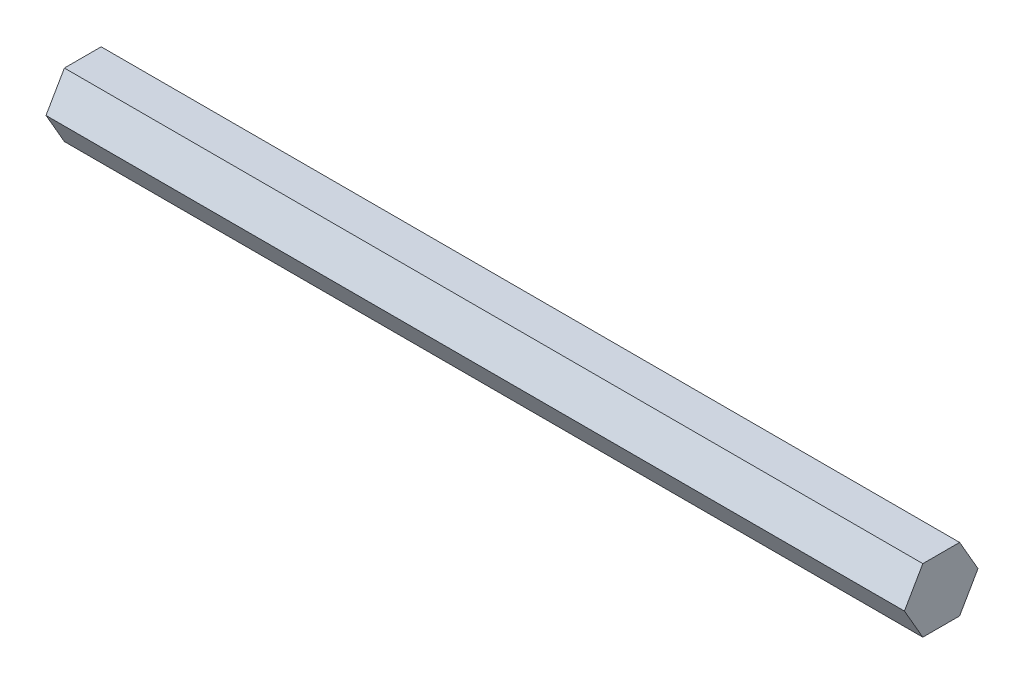
SolidWorks part; units mm, degrees
material "7075-T6 (SN)"
ref_plane "Front Plane" through (0, 0, 0) normal (0, 0, 1) x (1, 0, 0)
ref_plane "Top Plane" through (0, 0, 0) normal (0, 1, 0) x (1, 0, 0)
ref_plane "Right Plane" through (0, 0, 0) normal (1, 0, 0) x (0, 0, -1)
sketch "Sketch1" plane through (0, 0, 0) normal (1, 0, 0) x (0, 0, -1)
  line L1 (7.347, 0) -> (3.6735, 6.3627)
  line L2 (3.6735, 6.3627) -> (-3.6735, 6.3627)
  line L3 (-3.6735, 6.3627) -> (-7.347, 0)
  line L4 (-7.347, 0) -> (-3.6735, -6.3627)
  line L5 (-3.6735, -6.3627) -> (3.6735, -6.3627)
  line L6 (3.6735, -6.3627) -> (7.347, 0)
  circle A0 centre (0, 0) radius 6.3627 construction
  dimension "D1" = 12.7254
extrude "Boss-Extrude1" add sketch "Sketch1" along normal blind 171.45
